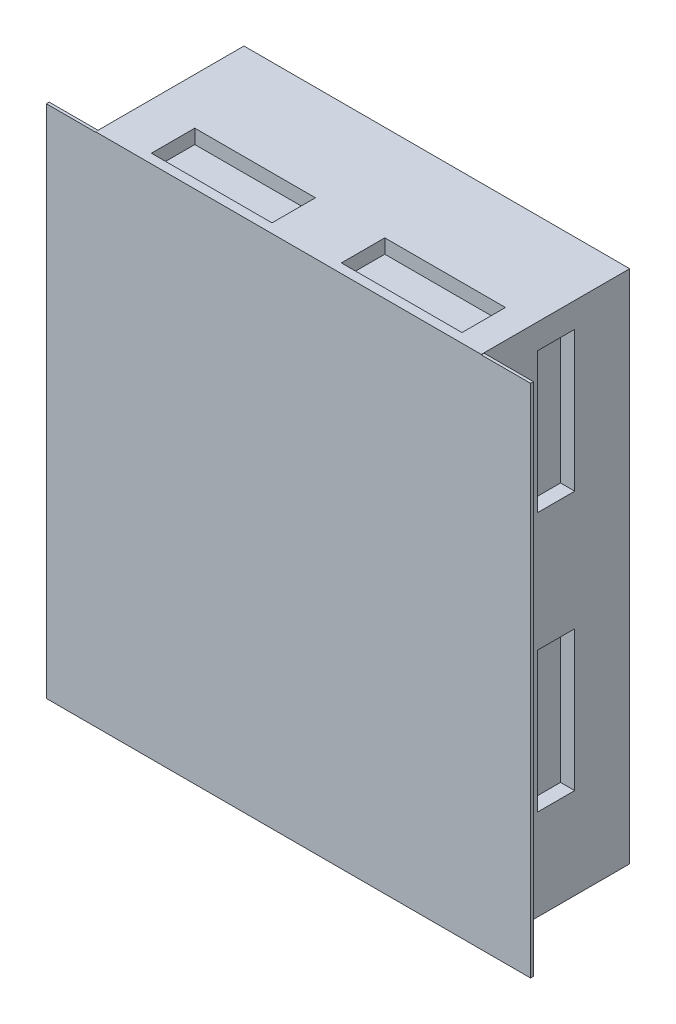
SolidWorks part; units mm, degrees
ref_plane "Front Plane" through (0, 0, 0) normal (0, 0, 1) x (1, 0, 0)
ref_plane "Top Plane" through (0, 0, 0) normal (0, 1, 0) x (1, 0, 0)
ref_plane "Right Plane" through (0, 0, 0) normal (1, 0, 0) x (0, 0, -1)
sketch "Sketch1" plane through (0, 0, 0) normal (0, 1, 0) x (1, 0, 0)
  line L0 (0, -55) -> (0, 55) construction
  line L1 (-67.95, -24.2613) -> (67.95, -24.2613)
  line L2 (-67.95, -24.2613) -> (-67.95, 28.0387)
  line L3 (-67.95, 28.0387) -> (67.95, 28.0387)
  line L4 (67.95, -24.2613) -> (67.95, 28.0387)
  line L5 (-67.95, -24.2613) -> (67.95, 28.0387) construction
  line L6 (-67.95, 28.0387) -> (67.95, -24.2613) construction
  point P0 (0, 1.8887)
  dimension "D1" = 135.9
  dimension "D2" = 52.3
extrude "Boss-Extrude1" add sketch "Sketch1" along normal blind 181.6
sketch "Sketch2" plane through (0, 0, 24.2613) normal (0, 0, 1) x (1, 0, 0)
  line L15 (-85.3, 181.4678) -> (85.3, 181.4678)
  line L17 (-85.3, 0) -> (85.3, 0)
  line L19 (28.765, 0) -> (-28.765, 0) construction
  line L21 (0, -28.765) -> (0, 28.765) construction
  line L22 (85.3, 181.4678) -> (85.3, 0)
  line L23 (-85.3, 181.4678) -> (-85.3, 0)
  point P3 (0, 181.4678)
  point P10 (0, 0)
  dimension "D2" = 170.6
  dimension "D1" = 170.6
extrude "Boss-Extrude2" add sketch "Sketch2" against normal blind 1
sketch "Sketch3" plane through (0, 0, -28.0387) normal (0, 0, -1) x (-1, 0, 0)
  line L0 (0, 0) -> (0, 181.6605) construction
  line L1 (0, 28.765) -> (0, -28.765) construction
  text T0 "               BMS" font "Century Gothic" height 12.7
extrude "Boss-Extrude3" add sketch "Sketch3" along normal blind 6
sketch "Sketch4" plane through (67.95, 0, 0) normal (1, 0, 0) x (0, 0, -1)
  line L1 (-4.5334, 32.0445) -> (8.6666, 32.0445)
  line L2 (-4.5334, 32.0445) -> (-4.5334, 81.4445)
  line L3 (-4.5334, 81.4445) -> (8.6666, 81.4445)
  line L4 (8.6666, 32.0445) -> (8.6666, 81.4445)
  line L5 (-4.5334, 123.398) -> (8.6666, 123.398)
  line L6 (-4.5334, 123.398) -> (-4.5334, 172.798)
  line L7 (-4.5334, 172.798) -> (8.6666, 172.798)
  line L8 (8.6666, 123.398) -> (8.6666, 172.798)
  dimension "D1" = 49.4
  dimension "D2" = 13.2
  dimension "D3" = 49.4
  dimension "D4" = 13.2
extrude "Cut-Extrude1" cut sketch "Sketch4" against normal blind 5
sketch "Sketch5" plane through (0, 181.6, 0) normal (0, 1, 0) x (1, 0, 0)
  line L1 (-51.5517, -5.6909) -> (-9.0517, -5.6909)
  line L2 (-51.5517, -5.6909) -> (-51.5517, -20.9909)
  line L3 (-51.5517, -20.9909) -> (-9.0517, -20.9909)
  line L4 (-9.0517, -5.6909) -> (-9.0517, -20.9909)
  line L5 (15.3886, -5.6909) -> (57.8886, -5.6909)
  line L6 (15.3886, -5.6909) -> (15.3886, -20.9909)
  line L7 (15.3886, -20.9909) -> (57.8886, -20.9909)
  line L8 (57.8886, -5.6909) -> (57.8886, -20.9909)
  dimension "D1" = 42.5
  dimension "D2" = 42.5
  dimension "D3" = 15.3
  dimension "D4" = 15.3
extrude "Cut-Extrude2" cut sketch "Sketch5" against normal blind 5
